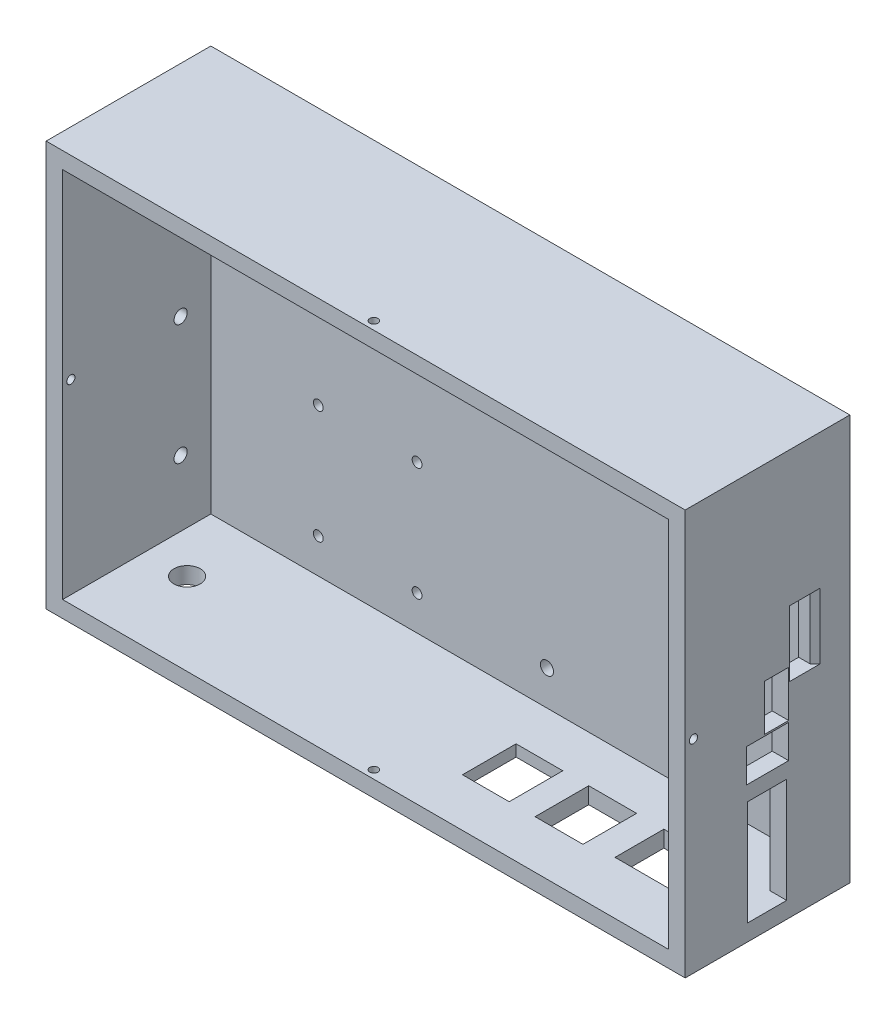
SolidWorks part; units mm, degrees
material "ABS generico"
ref_plane "Piano frontale" through (0, 0, 0) normal (0, 0, 1) x (1, 0, 0)
ref_plane "Piano superiore" through (0, 0, 0) normal (0, 1, 0) x (1, 0, 0)
ref_plane "Piano destro" through (0, 0, 0) normal (1, 0, 0) x (0, 0, -1)
sketch "Schizzo2" plane through (0, 0, 6.7032) normal (0, 0, 1) x (1, 0, 0)
  line L1 (-142.1241, 71.7669) -> (41.9232, 71.7669)
  line L2 (-142.1241, 71.7669) -> (-142.1241, -41.3)
  line L3 (-142.1241, -41.3) -> (41.9232, -41.3)
  line L4 (41.9232, 71.7669) -> (41.9232, -41.3)
extrude "Estrusione-Sottile1" add sketch "Schizzo2" against normal blind 45 thin thin type one direction wall 5
sketch "Schizzo3" plane through (0, 0, -38.2968) normal (0, 0, -1) x (-1, 0, 0)
  line L0 (147.1241, -46.3) -> (-46.9232, -46.3) construction
  line L1 (147.1241, -46.3) -> (-46.9232, -46.3)
  line L2 (147.1241, -46.3) -> (147.1241, 76.7669)
  line L3 (147.1241, 76.7669) -> (-46.9232, 76.7669)
  line L4 (-46.9232, -46.3) -> (-46.9232, 76.7669)
  line L5 (-46.9232, 76.7669) -> (147.1241, 76.7669) construction
extrude "Estrusione-Estrusione1" add sketch "Schizzo3" along normal blind 5
sketch "Schizzo4" plane through (0, 0, -38.2968) normal (0, 0, 1) x (1, 0, 0)
  circle A0 centre (-40.0515, 38.041) radius 2
  circle A1 centre (-40.0628, -30.759) radius 2
  circle A2 centre (31.3372, 38.041) radius 2
  circle A3 centre (31.3372, -30.759) radius 2
extrude "Taglio-Estrusione1" cut sketch "Schizzo4" against normal blind 5
chamfer "Smusso1" distance 1.5 angle 45 1 edges at (-38.0515, 38.041, -43.2968)
chamfer "Smusso2" distance 1.5 angle 45 1 edges at (33.3372, 38.041, -43.2968)
chamfer "Smusso3" distance 1.5 angle 45 1 edges at (33.3372, -30.759, -43.2968)
chamfer "Smusso4" distance 1.5 angle 45 1 edges at (-38.0628, -30.759, -43.2968)
sketch "Schizzo5" plane through (46.9232, 0, 0) normal (1, 0, 0) x (0, 0, -1)
  line L0 (38.2968, -41.3) -> (-6.7032, -41.3) construction
  line L1 (24.9835, 35.7347) -> (32.7511, 35.7347)
  line L2 (24.9835, 35.7347) -> (24.9835, 15.8135)
  line L3 (24.9835, 15.8135) -> (32.7511, 15.8135)
  line L4 (32.7511, 35.7347) -> (32.7511, 15.8135)
  line L5 (17.403, 19.7055) -> (24.7136, 19.7055)
  line L6 (17.403, 19.7055) -> (17.403, 5.7154)
  line L7 (17.403, 5.7154) -> (24.7136, 5.7154)
  line L8 (24.7136, 19.7055) -> (24.7136, 5.7154)
  line L9 (11.8754, 5.2263) -> (24.7136, 5.2263)
  line L10 (11.8754, 5.2263) -> (11.8754, -4.8505)
  line L11 (11.8754, -4.8505) -> (24.7136, -4.8505)
  line L12 (24.7136, 5.2263) -> (24.7136, -4.8505)
  line L13 (12.1622, -9.4223) -> (24.1123, -9.4223)
  line L14 (12.1622, -9.4223) -> (12.1622, -41.3)
  line L15 (12.1622, -41.3) -> (24.1123, -41.3)
  line L16 (24.1123, -9.4223) -> (24.1123, -41.3)
extrude "Taglio-Estrusione2" cut sketch "Schizzo5" against normal blind 5
sketch "Schizzo6" plane through (0, -46.3, 0) normal (0, -1, 0) x (1, 0, 0)
  line L1 (9.5415, -9.3749) -> (27.1048, -9.3749)
  line L2 (9.5415, -9.3749) -> (9.5415, -24.2129)
  line L3 (9.5415, -24.2129) -> (27.1048, -24.2129)
  line L4 (27.1048, -9.3749) -> (27.1048, -24.2129)
  line L5 (-13.2859, -7.9287) -> (1.2534, -7.9287)
  line L6 (-13.2859, -7.9287) -> (-13.2859, -24.2129)
  line L7 (-13.2859, -24.2129) -> (1.2534, -24.2129)
  line L8 (1.2534, -7.9287) -> (1.2534, -24.2129)
  line L9 (-35.3351, -7.9287) -> (-21.1563, -7.9287)
  line L10 (-35.3351, -7.9287) -> (-35.3351, -24.2129)
  line L11 (-35.3351, -24.2129) -> (-21.1563, -24.2129)
  line L12 (-21.1563, -7.9287) -> (-21.1563, -24.2129)
extrude "Taglio-Estrusione3" cut sketch "Schizzo6" against normal blind 5
chamfer "Smusso5" distance 1.5 angle 45 4 edges at (-21.1563, -46.3, -16.0708) (-28.2457, -46.3, -24.2129) (-35.3351, -46.3, -16.0708) (-28.2457, -46.3, -7.9287)
chamfer "Smusso6" distance 1.5 angle 45 1 edges at (46.9232, 25.7741, -32.7511)
sketch "Schizzo7" plane through (-147.1241, 0, 0) normal (-1, 0, 0) x (0, 0, 1)
  line L0 (-29.1347, 76.7669) -> (-29.1347, -46.3) construction
  line L1 (-43.2968, 76.7669) -> (6.7032, 76.7669) construction
  line L2 (-43.2968, -46.3) -> (6.7032, -46.3) construction
  circle A0 centre (-29.1347, 51.7669) radius 2
  circle A1 centre (-29.1347, 15.2334) radius 2
  circle A2 centre (-29.1347, -21.3) radius 2
  dimension "D2" = 4
  dimension "D3" = 4
  dimension "D4" = 4
  dimension "D1" = 25
  dimension "D5" = 25
extrude "Taglio-Estrusione4" cut sketch "Schizzo7" against normal blind 5
sketch "Schizzo8" plane through (-147.1241, 0, 0) normal (-1, 0, 0) x (0, 0, 1)
  line L0 (6.7032, 76.7669) -> (6.7032, -46.3) construction
  circle A0 centre (4.2032, 15.3098) radius 1.25
  dimension "D1" = 2.5
  dimension "D2" = 2.5
extrude "Taglio-Estrusione5" cut sketch "Schizzo8" against normal up to surface (194.0473 mm away)
sketch "Schizzo9" plane through (0, -46.3, 0) normal (0, -1, 0) x (1, 0, 0)
  line L0 (-147.1241, 6.7032) -> (46.9232, 6.7032) construction
  circle A0 centre (-50.1004, 4.2032) radius 1.25
  dimension "D1" = 2.5
  dimension "D2" = 2.5
extrude "Taglio-Estrusione6" cut sketch "Schizzo9" against normal up to surface (123.0669 mm away)
sketch "Schizzo10" plane through (0, 0, -43.2968) normal (0, 0, -1) x (-1, 0, 0)
  line L0 (-31.3372, 38.041) -> (140.4897, 38.041) construction
  line L1 (-31.3372, -30.759) -> (140.4897, -30.759) construction
  line L2 (140.4897, 38.041) -> (140.4897, 3.641) construction
  line L3 (140.4897, 3.641) -> (33.4246, 3.641) construction
  line L4 (140.4897, 20.841) -> (64.6644, 20.841) construction
  circle A0 centre (79.4863, 38.041) radius 1.5
  circle A1 centre (109.4863, 38.041) radius 1.5
  circle A2 centre (109.4863, -30.759) radius 1.5
  circle A3 centre (79.4863, -30.759) radius 1.5
  circle A4 centre (109.4863, 3.641) radius 1.5
  circle A5 centre (79.4863, 3.641) radius 1.5
  dimension "D1" = 3
  dimension "D2" = 3
  dimension "D3" = 30
extrude "Taglio-Estrusione7" cut sketch "Schizzo10" against normal blind 10
sketch "Schizzo11" plane through (0, -46.3, 0) normal (0, -1, 0) x (1, 0, 0)
  line L0 (-147.1241, -18.2968) -> (-72.6048, -18.2968) construction
  line L1 (-147.1241, -43.2968) -> (-147.1241, 6.7032) construction
  circle A0 centre (-129.3306, -18.2968) radius 4
  dimension "D1" = 8
extrude "Taglio-Estrusione8" cut sketch "Schizzo11" against normal blind 10
